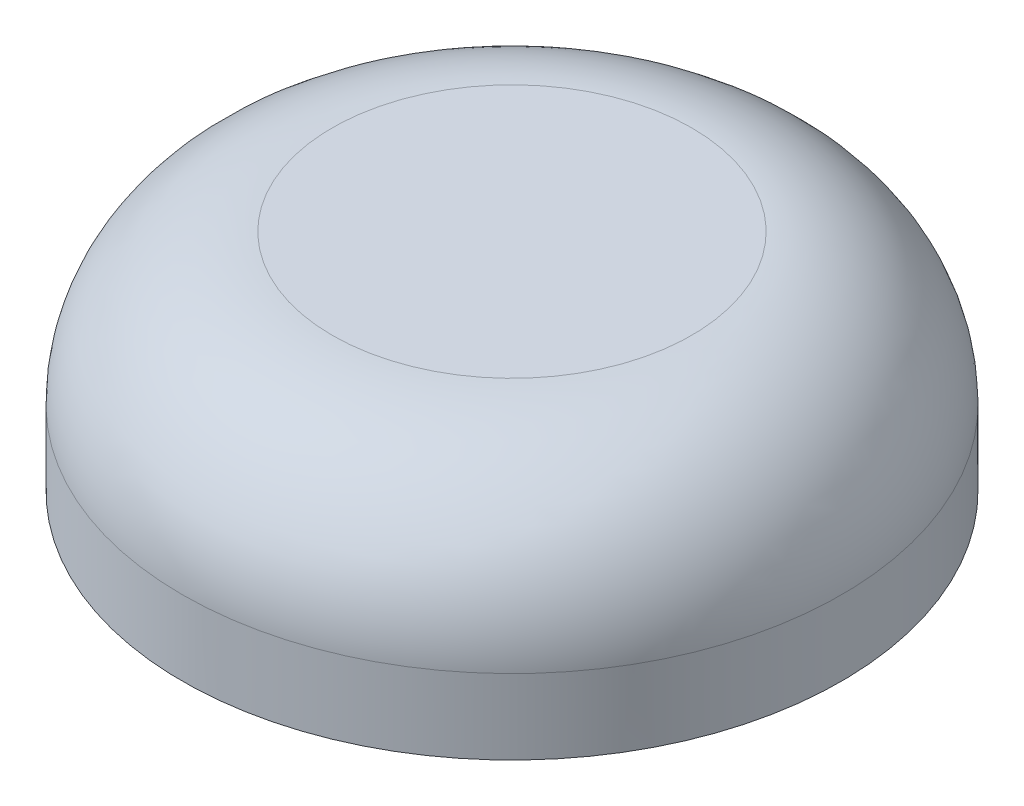
SolidWorks part; units mm, degrees
ref_plane "Front Plane" through (0, 0, 0) normal (0, 0, 1) x (1, 0, 0)
ref_plane "Top Plane" through (0, 0, 0) normal (0, 1, 0) x (1, 0, 0)
ref_plane "Right Plane" through (0, 0, 0) normal (1, 0, 0) x (0, 0, -1)
sketch "Sketch1" plane through (0, 0, 0) normal (0, 1, 0) x (1, 0, 0)
  circle A0 centre (0, 0) radius 5.588
extrude "Boss-Extrude1" add sketch "Sketch1" along normal blind 3.81
sketch "Sketch4" plane through (0, 0, 0) normal (0, -1, 0) x (1, 0, 0)
  circle A0 centre (0, 0) radius 1.27
extrude "Cut-Extrude1" cut sketch "Sketch4" against normal blind 2.54
fillet "Fillet5" radius 2.54 1 edges at (0, 3.81, 5.588)
